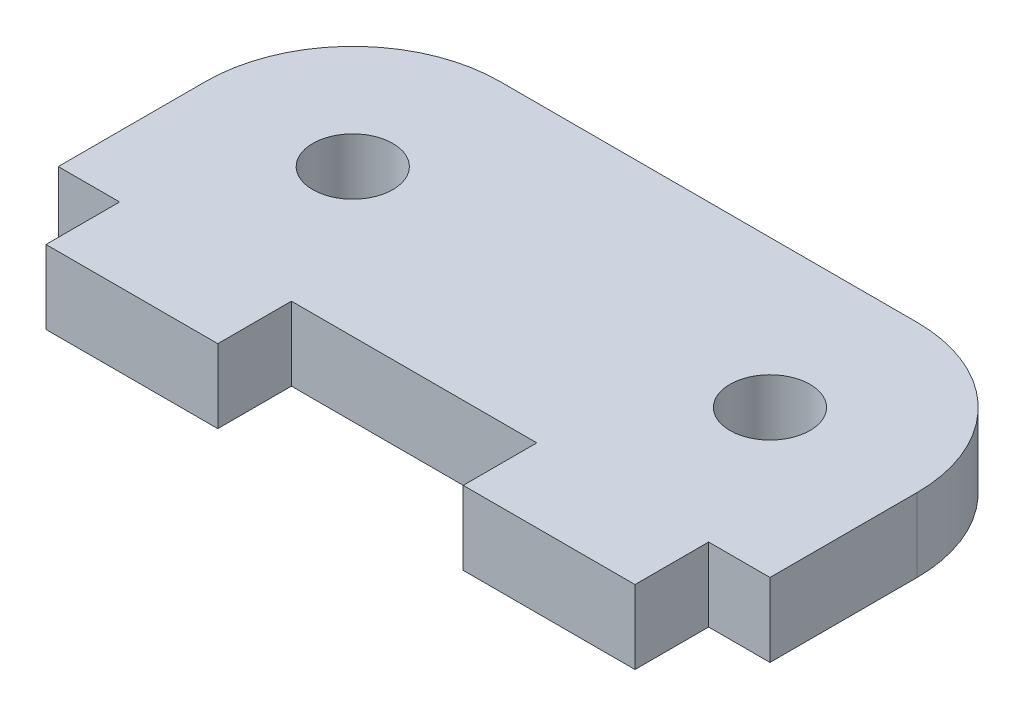
SolidWorks part; units mm, degrees
ref_plane "Front Plane" through (0, 0, 0) normal (0, 0, 1) x (1, 0, 0)
ref_plane "Top Plane" through (0, 0, 0) normal (0, 1, 0) x (1, 0, 0)
ref_plane "Right Plane" through (0, 0, 0) normal (1, 0, 0) x (0, 0, -1)
sketch "Sketch1" plane through (0, 0, 0) normal (0, 1, 0) x (1, 0, 0)
  line L0 (12, 3) -> (12, 15) construction
  line L1 (0, 0) -> (7, 0)
  line L2 (0, 0) -> (0, 3)
  line L3 (0, 3) -> (7, 3)
  line L4 (7, 0) -> (7, 3)
  line L5 (0, 3) -> (24, 3)
  line L7 (3.5, 15) -> (20.5, 15)
  line L9 (24, 3) -> (17, 3)
  line L10 (24, 3) -> (24, 0)
  line L11 (24, 0) -> (17, 0)
  line L12 (17, 3) -> (17, 0)
  line L13 (4.5, 9) -> (19.5, 9)
  line L15 (-2.5, 3) -> (26.5, 3)
  line L16 (-2.5, 3) -> (-2.5, 9)
  line L18 (26.5, 3) -> (26.5, 9)
  arc A0 (20.5, 15) -> (26.5, 9) centre (20.5, 9) cw
  arc A1 (-2.5, 9) -> (3.5, 15) centre (3.5, 9) cw
  point P16 (12, 9)
  point P18 (0, 0)
  point P21 (0, 0)
  point P24 (0, 0)
  point P25 (0, 0)
  point P26 (0, 0)
  dimension "D5" = 6
  dimension "D1" = 3
  dimension "D2" = 7
  dimension "D3" = 7
  dimension "D4" = 15
  dimension "D6" = 5
  dimension "D7" = 6
  dimension "D8" = 2.5
extrude "Boss-Extrude1" add sketch "Sketch1" along normal blind 3
hole_wizard "#4 Clearance Hole1" positions "Sketch2" profile "Sketch3" hole size "#4" standard "ANSI Inch" end condition through all
sketch "Sketch2" plane through (0, 3, 0) normal (0, 1, 0) x (1, 0, 0)
  point P0 (3.5, 9)
  point P2 (20.5, 9)
  point P5 (0, 0)
  point P7 (0, 0)
sketch "Sketch3" plane through (3.5, 3, -9) normal (1, 0, 0) x (0, 0, 1)
  line L0 (0, 0) -> (0, 3)
  line L1 (0, 3) -> (1.6319, 3)
  line L2 (1.6319, 3) -> (1.6319, 0)
  line L5 (1.6319, 0) -> (0, 0)
  line L11 (0, -6.35) -> (0, 107.95) construction
  dimension "Thru Hole Dia." = 3.2639
  dimension "Thru Hole Depth" = 3
